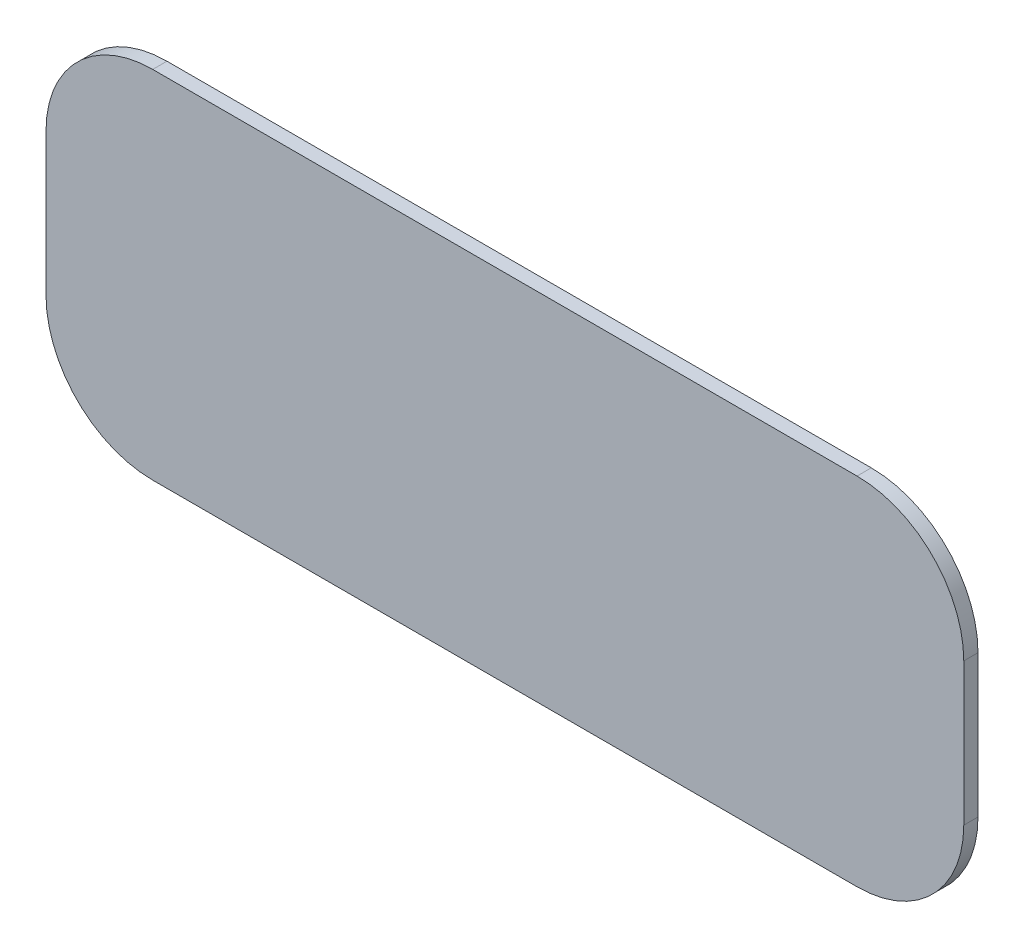
SolidWorks part; units mm, degrees
ref_plane "Plan de face" through (0, 0, 0) normal (0, 0, 1) x (1, 0, 0)
ref_plane "Plan de dessus" through (0, 0, 0) normal (0, 1, 0) x (1, 0, 0)
ref_plane "Plan de droite" through (0, 0, 0) normal (1, 0, 0) x (0, 0, -1)
sketch "Esquisse1" plane through (0, 0, 0) normal (0, 0, 1) x (1, 0, 0)
  line L1 (0, 0) -> (-129, 0)
  line L2 (0, 0) -> (0, 50)
  line L3 (0, 50) -> (-129, 50)
  line L4 (-129, 0) -> (-129, 50)
  dimension "D1" = 129
  dimension "D2" = 50
extrude "Boss.-Extru.1" add sketch "Esquisse1" along normal blind 2
fillet "Congé1" radius 15 4 edges at (-129, 0, 1) (0, 0, 1) (0, 50, 1) (-129, 50, 1)
sketch "Esquisse2" plane through (0, 0, 2) normal (0, 0, 1) x (1, 0, 0)
  circle A0 centre (-103.1168, 38.362) radius 2.5
  circle A1 centre (-27.3523, 38.362) radius 2.5
  circle A2 centre (-103.1168, 9.3994) radius 2.5
  circle A3 centre (-27.3523, 9.3994) radius 2.5
  dimension "D1" = 5
